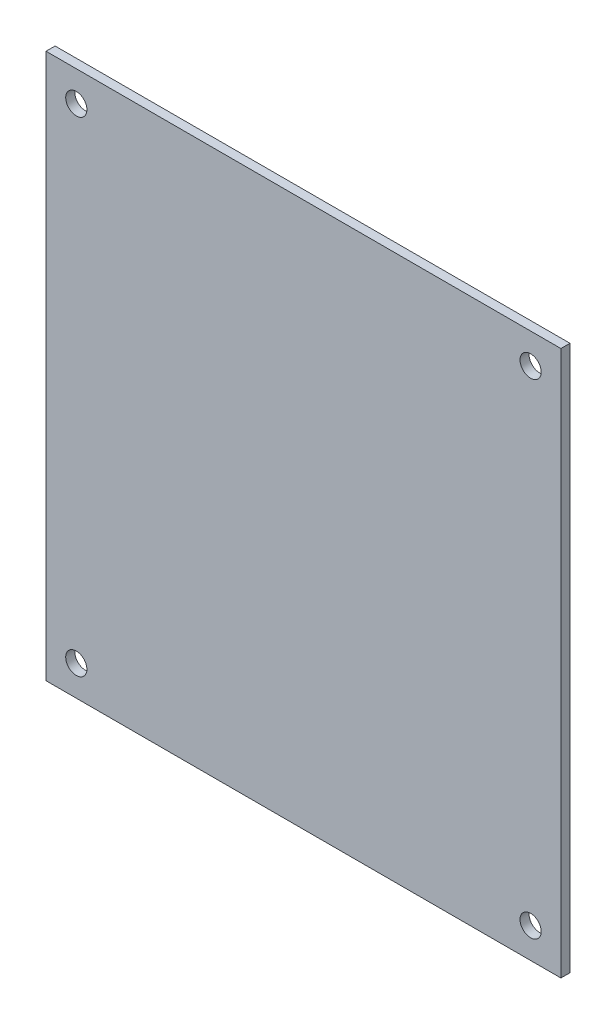
SolidWorks part; units mm, degrees
ref_plane "Спереди" through (0, 0, 0) normal (0, 0, 1) x (1, 0, 0)
ref_plane "Сверху" through (0, 0, 0) normal (0, 1, 0) x (1, 0, 0)
ref_plane "Справа" through (0, 0, 0) normal (1, 0, 0) x (0, 0, -1)
sketch "Эскиз1" plane through (0, 0, 0) normal (0, 0, 1) x (1, 0, 0)
  line L1 (-42.5, -45) -> (42.5, -45)
  line L2 (-42.5, -45) -> (-42.5, 45)
  line L3 (-42.5, 45) -> (42.5, 45)
  line L4 (42.5, -45) -> (42.5, 45)
  line L5 (-42.5, -45) -> (42.5, 45) construction
  line L6 (-42.5, 45) -> (42.5, -45) construction
  line L7 (-37.5, -40) -> (37.5, -40) construction
  line L8 (-37.5, -40) -> (-37.5, 40) construction
  line L9 (-37.5, 40) -> (37.5, 40) construction
  line L10 (37.5, -40) -> (37.5, 40) construction
  line L11 (-37.5, -40) -> (37.5, 40) construction
  line L12 (-37.5, 40) -> (37.5, -40) construction
  circle A2 centre (-37.5, 40) radius 1.75
  circle A3 centre (37.5, 40) radius 1.75
  circle A4 centre (37.5, -40) radius 1.75
  circle A5 centre (-37.5, -40) radius 1.75
  point P0 (0, 0)
  point P6 (0, 0)
  dimension "D3" = 3.5
  dimension "D1" = 85
  dimension "D2" = 90
  dimension "D4" = 5
  dimension "D5" = 5
extrude "Бобышка-Вытянуть1" add sketch "Эскиз1" along normal blind 1.5 contours L1 L4 L3 L2 A5 A4 A3 A2
